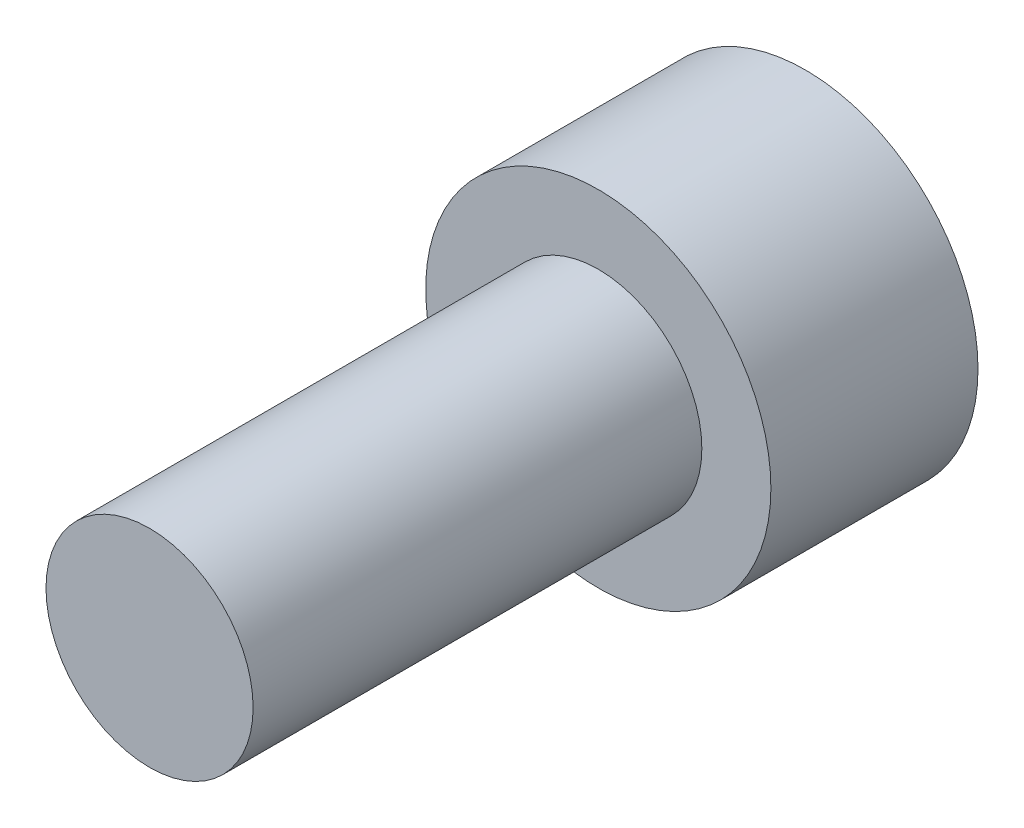
SolidWorks part; units mm, degrees
ref_plane "前视基准面" through (0, 0, 0) normal (0, 0, 1) x (1, 0, 0)
ref_plane "上视基准面" through (0, 0, 0) normal (0, 1, 0) x (1, 0, 0)
ref_plane "右视基准面" through (0, 0, 0) normal (1, 0, 0) x (0, 0, -1)
sketch "草图1" plane through (0, 0, 0) normal (0, 0, 1) x (1, 0, 0)
  circle A0 centre (0, 0) radius 5
  dimension "D1" = 10
extrude "凸台-拉伸1" add sketch "草图1" along normal blind 6
sketch "草图2" plane through (0, 0, 6) normal (0, 0, 1) x (1, 0, 0)
  circle A0 centre (0, 0) radius 3
  dimension "D1" = 6
extrude "凸台-拉伸2" add sketch "草图2" along normal blind 13
